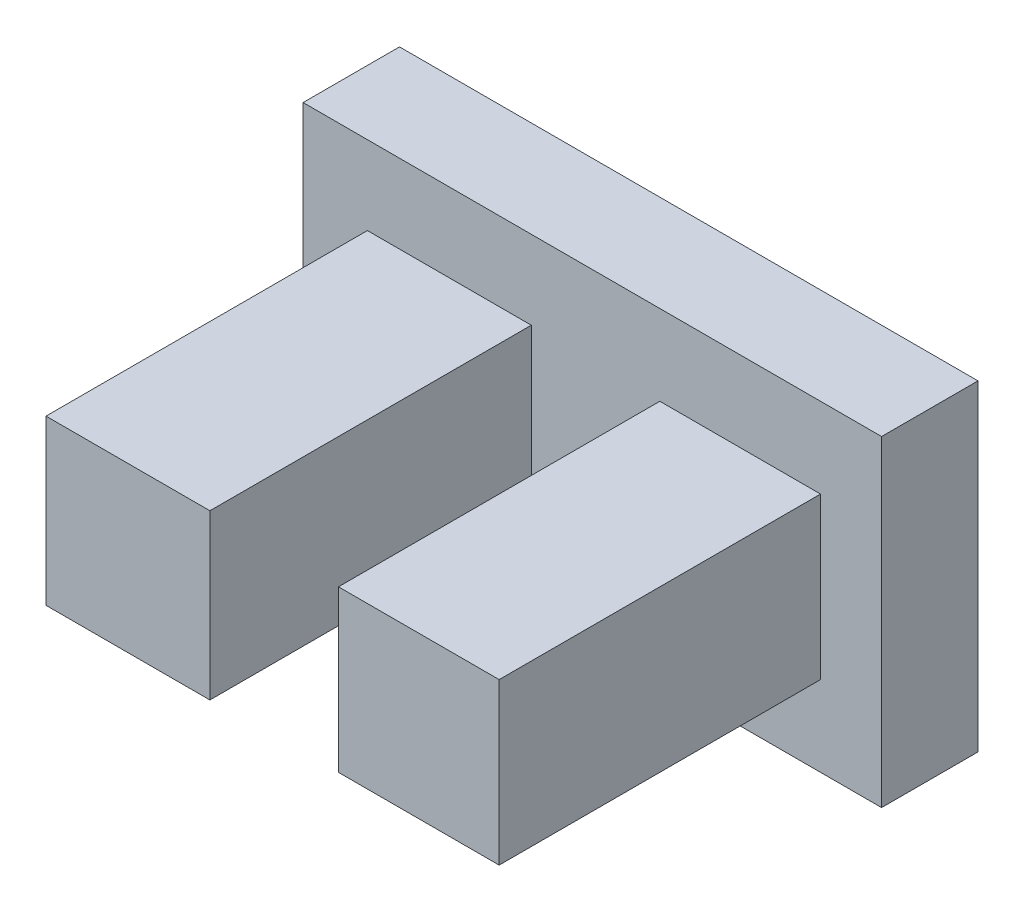
SolidWorks part; units mm, degrees
ref_plane "Front Plane" through (0, 0, 0) normal (0, 0, 1) x (1, 0, 0)
ref_plane "Top Plane" through (0, 0, 0) normal (0, 1, 0) x (1, 0, 0)
ref_plane "Right Plane" through (0, 0, 0) normal (1, 0, 0) x (0, 0, -1)
sketch "Sketch1" plane through (0, 0, 0) normal (0, 0, 1) x (1, 0, 0)
  line L1 (0, 0) -> (9, 0)
  line L2 (0, 0) -> (0, 5)
  line L3 (0, 5) -> (9, 5)
  line L4 (9, 0) -> (9, 5)
  dimension "D1" = 5
  dimension "D2" = 9
extrude "Boss-Extrude1" add sketch "Sketch1" along normal blind 1.5
sketch "Sketch2" plane through (0, 0, 1.5) normal (0, 0, 1) x (1, 0, 0)
  line L0 (0, 5) -> (0, 0) construction
  line L1 (1, 3.775) -> (3.55, 3.775)
  line L2 (1, 3.775) -> (1, 1.225)
  line L3 (1, 1.225) -> (3.55, 1.225)
  line L4 (3.55, 3.775) -> (3.55, 1.225)
  line L5 (9, 5) -> (0, 5) construction
  line L8 (5.55, 3.75) -> (8.05, 3.75)
  line L9 (5.55, 3.75) -> (5.55, 1.25)
  line L10 (5.55, 1.25) -> (8.05, 1.25)
  line L11 (8.05, 3.75) -> (8.05, 1.25)
  dimension "D1" = 2.55
  dimension "D2" = 2.55
  dimension "D3" = 1
  dimension "D4" = 1.225
  dimension "D5" = 2.5
  dimension "D6" = 2.5
  dimension "D7" = 1.25
  dimension "D8" = 2
extrude "Boss-Extrude2" add sketch "Sketch2" along normal blind 5
